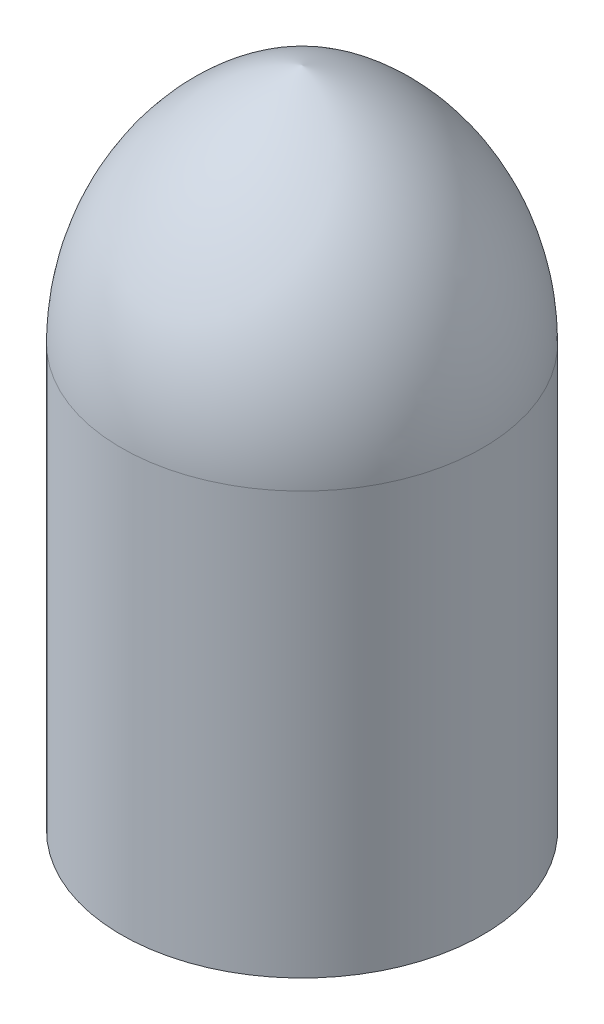
SolidWorks part; units mm, degrees
ref_plane "Front Plane" through (0, 0, 0) normal (0, 0, 1) x (1, 0, 0)
ref_plane "Top Plane" through (0, 0, 0) normal (0, 1, 0) x (1, 0, 0)
ref_plane "Right Plane" through (0, 0, 0) normal (1, 0, 0) x (0, 0, -1)
sketch "Sketch1" plane through (0, 0, 0) normal (0, 0, 1) x (1, 0, 0)
  line L0 (0, 0) -> (60, 0)
  line L1 (60, 0) -> (60, 140)
  line L2 (0, 220) -> (0, 0)
  arc A0 (60, 140) -> (0, 220) centre (-23.3333, 140) ccw
  point P6 (0, 0)
  point P7 (0, 0)
  point P8 (0, 0)
  point P9 (0, 0)
  point P10 (0, 0)
  point P11 (61.173, 136.9355)
  point P12 (0, 0)
  point P13 (0, 0)
  point P14 (0, 0)
  point P15 (64.3483, 134.7128)
  point P16 (0, 0)
  point P17 (0, 0)
  dimension "D2" = 60
  dimension "D1" = 220
  dimension "D3" = 140
revolve "Revolve2" add sketch "Sketch1" angle 360 about L2
shell "Shell3" thickness 2
